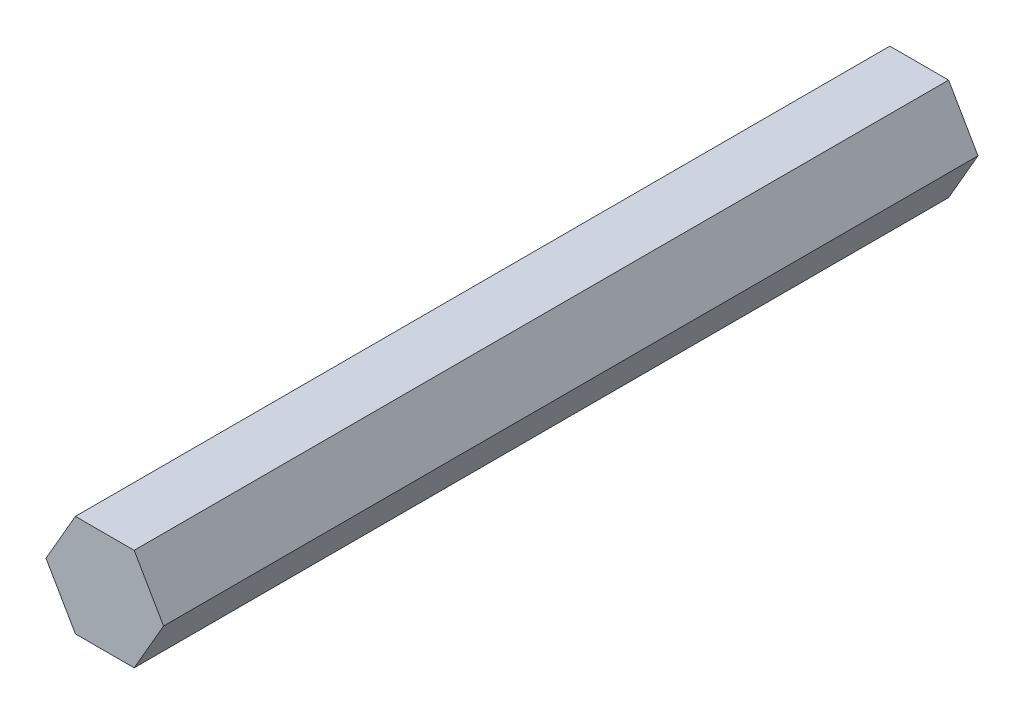
SolidWorks part; units mm, degrees
ref_plane "Front Plane" through (0, 0, 0) normal (0, 0, 1) x (1, 0, 0)
ref_plane "Top Plane" through (0, 0, 0) normal (0, 1, 0) x (1, 0, 0)
ref_plane "Right Plane" through (0, 0, 0) normal (1, 0, 0) x (0, 0, -1)
sketch "Sketch1" plane through (0, 0, 0) normal (0, 0, 1) x (1, 0, 0)
  line L1 (3.6662, -6.35) -> (7.3323, 0)
  line L2 (7.3323, 0) -> (3.6662, 6.35)
  line L3 (3.6662, 6.35) -> (-3.6662, 6.35)
  line L4 (-3.6662, 6.35) -> (-7.3323, 0)
  line L5 (-7.3323, 0) -> (-3.6662, -6.35)
  line L6 (-3.6662, -6.35) -> (3.6662, -6.35)
  circle A0 centre (0, 0) radius 6.35 construction
  dimension "D1" = 12.7
extrude "Boss-Extrude1" add sketch "Sketch1" along normal mid plane 101.6
